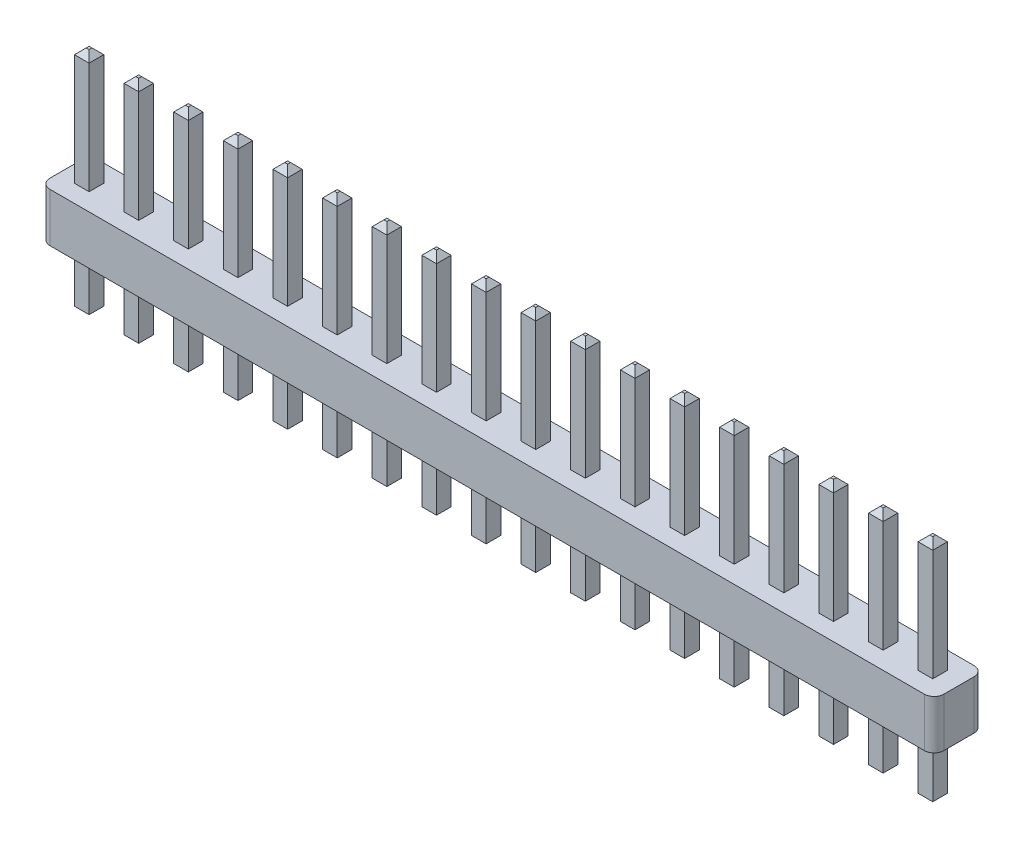
SolidWorks part; units mm, degrees
ref_plane "Front Plane" through (0, 0, 0) normal (0, 0, 1) x (1, 0, 0)
ref_plane "Top Plane" through (0, 0, 0) normal (0, 1, 0) x (1, 0, 0)
ref_plane "Right Plane" through (0, 0, 0) normal (1, 0, 0) x (0, 0, -1)
ref_plane "Plane1" through (0, 0, 0) normal (0, 1, 0) x (-1, 0, 0)
sketch "Sketch1" plane through (0, 0, 0) normal (0, 1, 0) x (-1, 0, 0)
  line L0 (-42.75, 1.27) -> (2, 1.27)
  line L1 (2.5, 0.77) -> (2.5, -0.77)
  line L2 (2, -1.27) -> (-42.75, -1.27)
  line L3 (-43.25, -0.77) -> (-43.25, 0.77)
  line L4 (0, 55) -> (0, -55) construction
  line L5 (55, 0) -> (-55, 0) construction
  arc A0 (2.5, 0.77) -> (2, 1.27) centre (2, 0.77) ccw
  arc A1 (2, -1.27) -> (2.5, -0.77) centre (2, -0.77) ccw
  arc A2 (-43.25, -0.77) -> (-42.75, -1.27) centre (-42.75, -0.77) ccw
  arc A3 (-42.75, 1.27) -> (-43.25, 0.77) centre (-42.75, 0.77) ccw
  dimension "D5" = 0.5
  dimension "D1" = 45.75
  dimension "D2" = 2.54
  dimension "D3" = 2.5
  dimension "D4" = 1.27
extrude "Boss-Extrude1" add sketch "Sketch1" along normal blind 2.5
ref_plane "Plane2" through (0, 0, 0) normal (0, 1, 0) x (-1, 0, 0)
sketch "Sketch2" plane through (0, 0, 0) normal (0, 1, 0) x (-1, 0, 0)
  line L0 (0.895, 0.375) -> (1.645, 0.375)
  line L1 (1.645, 0.375) -> (1.645, -0.375)
  line L2 (1.645, -0.375) -> (0.895, -0.375)
  line L3 (0.895, -0.375) -> (0.895, 0.375)
  line L4 (-0.895, -0.375) -> (-1.645, -0.375)
  line L5 (-1.645, -0.375) -> (-1.645, 0.375)
  line L6 (-1.645, 0.375) -> (-0.895, 0.375)
  line L7 (-0.895, 0.375) -> (-0.895, -0.375)
  line L8 (-1.645, 0.375) -> (-0.895, -0.375) construction
  line L9 (0.895, -0.375) -> (1.645, 0.375) construction
  line L10 (1.375, 0) -> (-1.375, 0) construction
  line L11 (0, 1.375) -> (0, -1.375) construction
  line L12 (-4.185, 0.375) -> (-3.435, 0.375)
  line L13 (-3.435, 0.375) -> (-3.435, -0.375)
  line L14 (-3.435, -0.375) -> (-4.185, -0.375)
  line L15 (-4.185, -0.375) -> (-4.185, 0.375)
  line L16 (-5.975, -0.375) -> (-6.725, -0.375)
  line L17 (-6.725, -0.375) -> (-6.725, 0.375)
  line L18 (-6.725, 0.375) -> (-5.975, 0.375)
  line L19 (-5.975, 0.375) -> (-5.975, -0.375)
  line L20 (-6.725, 0.375) -> (-5.975, -0.375) construction
  line L21 (-4.185, -0.375) -> (-3.435, 0.375) construction
  line L22 (-9.265, 0.375) -> (-8.515, 0.375)
  line L23 (-8.515, 0.375) -> (-8.515, -0.375)
  line L24 (-8.515, -0.375) -> (-9.265, -0.375)
  line L25 (-9.265, -0.375) -> (-9.265, 0.375)
  line L26 (-11.055, -0.375) -> (-11.805, -0.375)
  line L27 (-11.805, -0.375) -> (-11.805, 0.375)
  line L28 (-11.805, 0.375) -> (-11.055, 0.375)
  line L29 (-11.055, 0.375) -> (-11.055, -0.375)
  line L30 (-11.805, 0.375) -> (-11.055, -0.375) construction
  line L31 (-9.265, -0.375) -> (-8.515, 0.375) construction
  line L32 (-14.345, 0.375) -> (-13.595, 0.375)
  line L33 (-13.595, 0.375) -> (-13.595, -0.375)
  line L34 (-13.595, -0.375) -> (-14.345, -0.375)
  line L35 (-14.345, -0.375) -> (-14.345, 0.375)
  line L36 (-16.135, -0.375) -> (-16.885, -0.375)
  line L37 (-16.885, -0.375) -> (-16.885, 0.375)
  line L38 (-16.885, 0.375) -> (-16.135, 0.375)
  line L39 (-16.135, 0.375) -> (-16.135, -0.375)
  line L40 (-16.885, 0.375) -> (-16.135, -0.375) construction
  line L41 (-14.345, -0.375) -> (-13.595, 0.375) construction
  line L42 (-19.425, 0.375) -> (-18.675, 0.375)
  line L43 (-18.675, 0.375) -> (-18.675, -0.375)
  line L44 (-18.675, -0.375) -> (-19.425, -0.375)
  line L45 (-19.425, -0.375) -> (-19.425, 0.375)
  line L46 (-21.215, -0.375) -> (-21.965, -0.375)
  line L47 (-21.965, -0.375) -> (-21.965, 0.375)
  line L48 (-21.965, 0.375) -> (-21.215, 0.375)
  line L49 (-21.215, 0.375) -> (-21.215, -0.375)
  line L50 (-21.965, 0.375) -> (-21.215, -0.375) construction
  line L51 (-19.425, -0.375) -> (-18.675, 0.375) construction
  line L52 (-24.505, 0.375) -> (-23.755, 0.375)
  line L53 (-23.755, 0.375) -> (-23.755, -0.375)
  line L54 (-23.755, -0.375) -> (-24.505, -0.375)
  line L55 (-24.505, -0.375) -> (-24.505, 0.375)
  line L56 (-26.295, -0.375) -> (-27.045, -0.375)
  line L57 (-27.045, -0.375) -> (-27.045, 0.375)
  line L58 (-27.045, 0.375) -> (-26.295, 0.375)
  line L59 (-26.295, 0.375) -> (-26.295, -0.375)
  line L60 (-27.045, 0.375) -> (-26.295, -0.375) construction
  line L61 (-24.505, -0.375) -> (-23.755, 0.375) construction
  line L62 (-29.585, 0.375) -> (-28.835, 0.375)
  line L63 (-28.835, 0.375) -> (-28.835, -0.375)
  line L64 (-28.835, -0.375) -> (-29.585, -0.375)
  line L65 (-29.585, -0.375) -> (-29.585, 0.375)
  line L66 (-31.375, -0.375) -> (-32.125, -0.375)
  line L67 (-32.125, -0.375) -> (-32.125, 0.375)
  line L68 (-32.125, 0.375) -> (-31.375, 0.375)
  line L69 (-31.375, 0.375) -> (-31.375, -0.375)
  line L70 (-32.125, 0.375) -> (-31.375, -0.375) construction
  line L71 (-29.585, -0.375) -> (-28.835, 0.375) construction
  line L72 (-34.665, 0.375) -> (-33.915, 0.375)
  line L73 (-33.915, 0.375) -> (-33.915, -0.375)
  line L74 (-33.915, -0.375) -> (-34.665, -0.375)
  line L75 (-34.665, -0.375) -> (-34.665, 0.375)
  line L76 (-36.455, -0.375) -> (-37.205, -0.375)
  line L77 (-37.205, -0.375) -> (-37.205, 0.375)
  line L78 (-37.205, 0.375) -> (-36.455, 0.375)
  line L79 (-36.455, 0.375) -> (-36.455, -0.375)
  line L80 (-37.205, 0.375) -> (-36.455, -0.375) construction
  line L81 (-34.665, -0.375) -> (-33.915, 0.375) construction
  line L82 (-39.745, 0.375) -> (-38.995, 0.375)
  line L83 (-38.995, 0.375) -> (-38.995, -0.375)
  line L84 (-38.995, -0.375) -> (-39.745, -0.375)
  line L85 (-39.745, -0.375) -> (-39.745, 0.375)
  line L86 (-41.535, -0.375) -> (-42.285, -0.375)
  line L87 (-42.285, -0.375) -> (-42.285, 0.375)
  line L88 (-42.285, 0.375) -> (-41.535, 0.375)
  line L89 (-41.535, 0.375) -> (-41.535, -0.375)
  line L90 (-42.285, 0.375) -> (-41.535, -0.375) construction
  line L91 (-39.745, -0.375) -> (-38.995, 0.375) construction
  point P8 (-1.27, 0)
  point P9 (1.27, 0)
  point P24 (-6.35, 0)
  point P25 (-3.81, 0)
  point P34 (-11.43, 0)
  point P35 (-8.89, 0)
  point P44 (-16.51, 0)
  point P45 (-13.97, 0)
  point P54 (-21.59, 0)
  point P55 (-19.05, 0)
  point P64 (-26.67, 0)
  point P65 (-24.13, 0)
  point P74 (-31.75, 0)
  point P75 (-29.21, 0)
  point P84 (-36.83, 0)
  point P85 (-34.29, 0)
  point P94 (-41.91, 0)
  point P95 (-39.37, 0)
  dimension "D1" = 2.54
  dimension "D2" = 0.75
  dimension "D3" = 1.27
  dimension "D4" = 9
extrude "Boss-Extrude2" add sketch "Sketch2" along normal blind 8.5 and the other way blind 3.25
chamfer "Chamfer1" distance 0.3 angle 45 144 edges at (-1.645, 8.5, 0) (-1.27, 8.5, -0.375) (-0.895, 8.5, 0) (-1.27, 8.5, 0.375) (0.895, 8.5, 0) (1.27, 8.5, -0.375) (1.645, 8.5, 0) (1.27, 8.5, 0.375) (1.27, -3.25, -0.375) (1.645, -3.25, 0) (0.895, -3.25, 0) (1.27, -3.25, 0.375) (-1.27, -3.25, 0.375) (-1.645, -3.25, 0) (-0.895, -3.25, 0) (-1.27, -3.25, -0.375) (3.81, -3.25, -0.375) (3.435, -3.25, 0) (3.81, -3.25, 0.375) (4.185, -3.25, 0) (6.35, -3.25, 0.375) (6.725, -3.25, 0) (6.35, -3.25, -0.375) (5.975, -3.25, 0) (8.89, -3.25, -0.375) (8.515, -3.25, 0) (8.89, -3.25, 0.375) (9.265, -3.25, 0) (11.43, -3.25, 0.375) (11.805, -3.25, 0) (11.43, -3.25, -0.375) (11.055, -3.25, 0) (13.97, -3.25, -0.375) (13.595, -3.25, 0) (13.97, -3.25, 0.375) (14.345, -3.25, 0) (16.51, -3.25, 0.375) (16.885, -3.25, 0) (16.51, -3.25, -0.375) (16.135, -3.25, 0) (19.05, -3.25, -0.375) (18.675, -3.25, 0) (19.05, -3.25, 0.375) (19.425, -3.25, 0) (21.59, -3.25, 0.375) (21.965, -3.25, 0) (21.59, -3.25, -0.375) (21.215, -3.25, 0) (24.13, -3.25, -0.375) (23.755, -3.25, 0) (24.13, -3.25, 0.375) (24.505, -3.25, 0) (26.67, -3.25, 0.375) (27.045, -3.25, 0) (26.67, -3.25, -0.375) (26.295, -3.25, 0) (29.21, -3.25, -0.375) (28.835, -3.25, 0) (29.21, -3.25, 0.375) (29.585, -3.25, 0) (31.75, -3.25, 0.375) (32.125, -3.25, 0) (31.75, -3.25, -0.375) (31.375, -3.25, 0) (34.29, -3.25, -0.375) (33.915, -3.25, 0) (34.29, -3.25, 0.375) (34.665, -3.25, 0) (36.83, -3.25, 0.375) (37.205, -3.25, 0) (36.83, -3.25, -0.375) (36.455, -3.25, 0) (39.37, -3.25, -0.375) (38.995, -3.25, 0) (39.37, -3.25, 0.375) (39.745, -3.25, 0) (41.91, -3.25, 0.375) (42.285, -3.25, 0) (41.91, -3.25, -0.375) (41.535, -3.25, 0) (41.91, 8.5, -0.375) (42.285, 8.5, 0) (41.91, 8.5, 0.375) (41.535, 8.5, 0) (39.37, 8.5, 0.375) (38.995, 8.5, 0) (39.37, 8.5, -0.375) (39.745, 8.5, 0) (36.83, 8.5, -0.375) (37.205, 8.5, 0) (36.83, 8.5, 0.375) (36.455, 8.5, 0) (34.29, 8.5, 0.375) (33.915, 8.5, 0) (34.29, 8.5, -0.375) (34.665, 8.5, 0) (31.75, 8.5, -0.375) (32.125, 8.5, 0) (31.75, 8.5, 0.375) (31.375, 8.5, 0) (29.21, 8.5, 0.375) (28.835, 8.5, 0) (29.21, 8.5, -0.375) (29.585, 8.5, 0) (26.67, 8.5, -0.375) (27.045, 8.5, 0) (26.67, 8.5, 0.375) (26.295, 8.5, 0) (24.13, 8.5, 0.375) (23.755, 8.5, 0) (24.13, 8.5, -0.375) (24.505, 8.5, 0) (21.59, 8.5, -0.375) (21.965, 8.5, 0) (21.59, 8.5, 0.375) (21.215, 8.5, 0) (19.05, 8.5, 0.375) (18.675, 8.5, 0) (19.05, 8.5, -0.375) (19.425, 8.5, 0) (16.51, 8.5, -0.375) (16.885, 8.5, 0) (16.51, 8.5, 0.375) (16.135, 8.5, 0) (13.97, 8.5, 0.375) (13.595, 8.5, 0) (13.97, 8.5, -0.375) (14.345, 8.5, 0) (11.43, 8.5, -0.375) (11.805, 8.5, 0) (11.43, 8.5, 0.375) (11.055, 8.5, 0) (8.89, 8.5, 0.375) (8.515, 8.5, 0) (8.89, 8.5, -0.375) (9.265, 8.5, 0) (6.35, 8.5, -0.375) (6.725, 8.5, 0) (6.35, 8.5, 0.375) (5.975, 8.5, 0) (3.81, 8.5, -0.375) (3.81, 8.5, 0.375) (3.435, 8.5, 0) (4.185, 8.5, 0)
